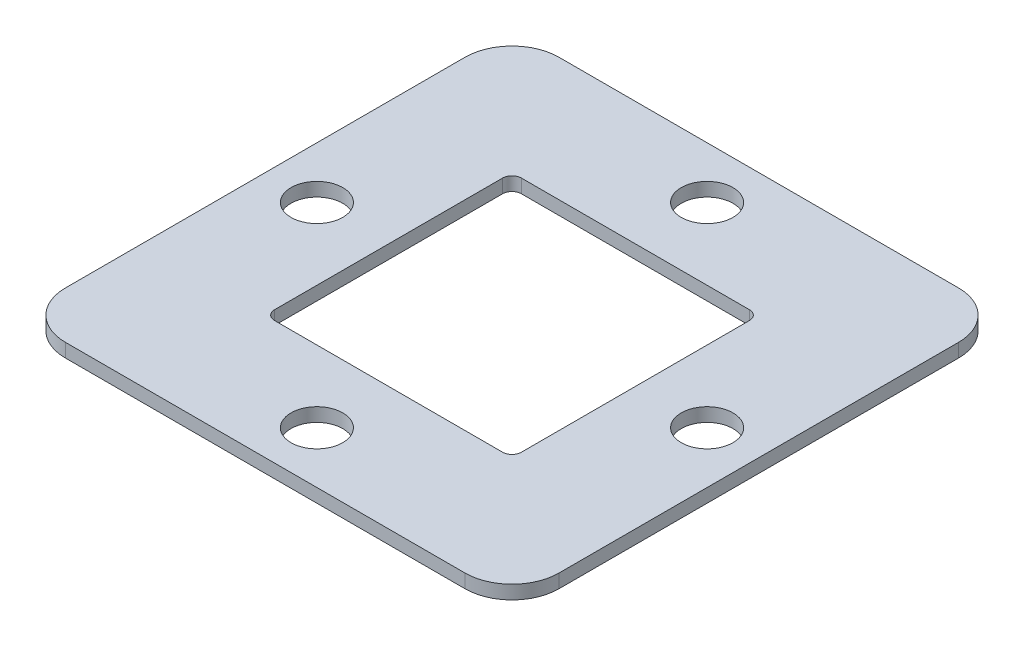
SolidWorks part; units mm, degrees
material "Custom Plastic"
ref_plane "Front Plane" through (0, 0, 0) normal (0, 0, 1) x (1, 0, 0)
ref_plane "Top Plane" through (0, 0, 0) normal (0, 1, 0) x (1, 0, 0)
ref_plane "Right Plane" through (0, 0, 0) normal (1, 0, 0) x (0, 0, -1)
sketch "Sketch1" plane through (0, 0, 0) normal (0, 1, 0) x (1, 0, 0)
  line L5 (-10.5, 10.5) -> (10.5, 10.5)
  line L6 (-10.5, 10.5) -> (-10.5, -10.5)
  line L7 (-10.5, -10.5) -> (10.5, -10.5)
  line L8 (10.5, 10.5) -> (10.5, -10.5)
  line L9 (-10.5, 10.5) -> (10.5, -10.5) construction
  line L10 (-10.5, -10.5) -> (10.5, 10.5) construction
  point P0 (0, 0)
  dimension "D1" = 21
extrude "Boss-Extrude1" add sketch "Sketch1" along normal blind 0.58
sketch "Sketch2" plane through (0, 0.58, 0) normal (0, 1, 0) x (1, 0, 0)
  line L5 (-5.25, 5.25) -> (5.25, 5.25)
  line L6 (-5.25, 5.25) -> (-5.25, -5.25)
  line L7 (-5.25, -5.25) -> (5.25, -5.25)
  line L8 (5.25, 5.25) -> (5.25, -5.25)
  line L9 (-5.25, 5.25) -> (5.25, -5.25) construction
  line L10 (-5.25, -5.25) -> (5.25, 5.25) construction
  point P0 (0, 0)
  dimension "D1" = 10.5
extrude "Cut-Extrude1" cut sketch "Sketch2" against normal through all
fillet "Fillet1" radius 2 4 edges at (-10.5, 0.29, 10.5) (-10.5, 0.29, -10.5) (10.5, 0.29, -10.5) (10.5, 0.29, 10.5)
sketch "Sketch3" plane through (0, 0.58, 0) normal (0, 1, 0) x (1, 0, 0)
  line L0 (-1000, 0) -> (49000, 0) construction
  line L1 (0, -1000) -> (0, 49000) construction
  line L2 (-1000.1511, 5.5) -> (48999.7528, 5.5) construction
  line L3 (-999.6259, -5.5) -> (49000.7521, -5.5) construction
  line L4 (-1006.7067, 2.2) -> (48970.3156, 2.2) construction
  line L5 (-995.6657, -2.2) -> (48999.0786, -2.2) construction
  line L8 (6.3218, 3.3211) -> (6.6489, 4.535)
  line L10 (5.25, 1.9) -> (5.25, 1.79)
  line L12 (7.2282, 4.3789) -> (6.9011, 3.165)
  line L43 (7.0073, 3.1364) -> (7.3345, 4.3502)
  line L45 (6.5427, 4.5636) -> (6.2155, 3.3498)
  line L48 (10.5, 6) -> (10.5, 5) construction
  line L49 (8.3, 5.91) -> (9, 6.64)
  line L137 (9, 6) -> (8.3, 5.8)
  line L138 (8.3, 5.2) -> (9, 5)
  line L140 (9, 4.36) -> (8.3, 5.09)
  line L141 (8.3, 5.8) -> (8.3, 5.2) construction
  line L224 (5.25, 2.5) -> (5.25, 1.9) construction
  line L312 (5.25, 2.61) -> (5.25, 2.5)
  line L314 (10.5, 6.64) -> (9, 6.64)
  line L315 (10.5, 6.64) -> (10.5, 6)
  line L316 (10.5, 6) -> (9, 6)
  line L319 (10.5, 5) -> (9, 5)
  line L320 (10.5, 5) -> (10.5, 4.36)
  line L321 (10.5, 4.36) -> (9, 4.36)
  line L433 (10.5, -8.5) -> (10.5, 8.5) construction
  line L434 (5.25, -5.25) -> (5.25, 5.25) construction
  line L435 (10.5, -5) -> (10.5, -4.36)
  line L436 (10.5, -5) -> (9, -5)
  line L437 (10.5, -4.36) -> (9, -4.36)
  line L438 (9, -4.36) -> (8.3, -5.09)
  line L439 (8.3, -5.2) -> (9, -5)
  line L440 (7.2282, -4.3789) -> (6.9011, -3.165)
  line L441 (7.0073, -3.1364) -> (7.3345, -4.3502)
  line L442 (5.25, -1.9) -> (5.25, -1.79)
  line L443 (5.25, -2.61) -> (5.25, -2.5)
  line L444 (6.5427, -4.5636) -> (6.2155, -3.3498)
  line L445 (6.3218, -3.3211) -> (6.6489, -4.535)
  line L446 (10.5, -6.64) -> (9, -6.64)
  line L447 (8.3, -5.91) -> (9, -6.64)
  line L448 (9, -6) -> (8.3, -5.8)
  line L449 (10.5, -6) -> (9, -6)
  line L450 (10.5, -6.64) -> (10.5, -6)
  line L451 (-5, -10.5) -> (-4.36, -10.5)
  line L452 (-5, -10.5) -> (-5, -9)
  line L453 (-4.36, -10.5) -> (-4.36, -9)
  line L454 (-4.36, -9) -> (-5.09, -8.3)
  line L455 (-5.2, -8.3) -> (-5, -9)
  line L456 (-4.3789, -7.2282) -> (-3.165, -6.9011)
  line L457 (-3.1364, -7.0073) -> (-4.3502, -7.3345)
  line L458 (-1.9, -5.25) -> (-1.79, -5.25)
  line L459 (-2.61, -5.25) -> (-2.5, -5.25)
  line L460 (-4.5636, -6.5427) -> (-3.3498, -6.2155)
  line L461 (-3.3211, -6.3218) -> (-4.535, -6.6489)
  line L462 (-6.64, -10.5) -> (-6.64, -9)
  line L463 (-5.91, -8.3) -> (-6.64, -9)
  line L464 (-6, -9) -> (-5.8, -8.3)
  line L465 (-6, -10.5) -> (-6, -9)
  line L466 (-6.64, -10.5) -> (-6, -10.5)
  line L467 (6.64, -10.5) -> (6, -10.5)
  line L468 (6.64, -10.5) -> (6.64, -9)
  line L469 (5.91, -8.3) -> (6.64, -9)
  line L470 (6, -9) -> (5.8, -8.3)
  line L471 (6, -10.5) -> (6, -9)
  line L472 (4.5636, -6.5427) -> (3.3498, -6.2155)
  line L473 (3.3211, -6.3218) -> (4.535, -6.6489)
  line L474 (2.61, -5.25) -> (2.5, -5.25)
  line L475 (1.9, -5.25) -> (1.79, -5.25)
  line L476 (4.3789, -7.2282) -> (3.165, -6.9011)
  line L477 (3.1364, -7.0073) -> (4.3502, -7.3345)
  line L478 (5.2, -8.3) -> (5, -9)
  line L479 (5, -10.5) -> (5, -9)
  line L480 (5, -10.5) -> (4.36, -10.5)
  line L481 (4.36, -10.5) -> (4.36, -9)
  line L482 (4.36, -9) -> (5.09, -8.3)
  line L483 (-10.5, 5) -> (-10.5, 4.36)
  line L484 (-10.5, 5) -> (-9, 5)
  line L485 (-10.5, 4.36) -> (-9, 4.36)
  line L486 (-9, 4.36) -> (-8.3, 5.09)
  line L487 (-8.3, 5.2) -> (-9, 5)
  line L488 (-7.2282, 4.3789) -> (-6.9011, 3.165)
  line L489 (-7.0073, 3.1364) -> (-7.3345, 4.3502)
  line L490 (-5.25, 1.9) -> (-5.25, 1.79)
  line L491 (-5.25, 2.61) -> (-5.25, 2.5)
  line L492 (-6.5427, 4.5636) -> (-6.2155, 3.3498)
  line L493 (-6.3218, 3.3211) -> (-6.6489, 4.535)
  line L494 (-10.5, 6.64) -> (-9, 6.64)
  line L495 (-8.3, 5.91) -> (-9, 6.64)
  line L496 (-9, 6) -> (-8.3, 5.8)
  line L497 (-10.5, 6) -> (-9, 6)
  line L498 (-10.5, 6.64) -> (-10.5, 6)
  line L499 (-10.5, -6.64) -> (-10.5, -6)
  line L500 (-10.5, -6.64) -> (-9, -6.64)
  line L501 (-8.3, -5.91) -> (-9, -6.64)
  line L502 (-9, -6) -> (-8.3, -5.8)
  line L503 (-10.5, -6) -> (-9, -6)
  line L504 (-6.5427, -4.5636) -> (-6.2155, -3.3498)
  line L505 (-6.3218, -3.3211) -> (-6.6489, -4.535)
  line L506 (-5.25, -2.61) -> (-5.25, -2.5)
  line L507 (-5.25, -1.9) -> (-5.25, -1.79)
  line L508 (-7.2282, -4.3789) -> (-6.9011, -3.165)
  line L509 (-7.0073, -3.1364) -> (-7.3345, -4.3502)
  line L510 (-8.3, -5.2) -> (-9, -5)
  line L511 (-10.5, -5) -> (-9, -5)
  line L512 (-10.5, -5) -> (-10.5, -4.36)
  line L513 (-10.5, -4.36) -> (-9, -4.36)
  line L514 (-9, -4.36) -> (-8.3, -5.09)
  line L515 (5, 10.5) -> (4.36, 10.5)
  line L516 (5, 10.5) -> (5, 9)
  line L517 (4.36, 10.5) -> (4.36, 9)
  line L518 (4.36, 9) -> (5.09, 8.3)
  line L519 (5.2, 8.3) -> (5, 9)
  line L520 (4.3789, 7.2282) -> (3.165, 6.9011)
  line L521 (3.1364, 7.0073) -> (4.3502, 7.3345)
  line L522 (1.9, 5.25) -> (1.79, 5.25)
  line L523 (2.61, 5.25) -> (2.5, 5.25)
  line L524 (4.5636, 6.5427) -> (3.3498, 6.2155)
  line L525 (3.3211, 6.3218) -> (4.535, 6.6489)
  line L526 (6.64, 10.5) -> (6.64, 9)
  line L527 (5.91, 8.3) -> (6.64, 9)
  line L528 (6, 9) -> (5.8, 8.3)
  line L529 (6, 10.5) -> (6, 9)
  line L530 (6.64, 10.5) -> (6, 10.5)
  line L531 (-6.64, 10.5) -> (-6, 10.5)
  line L532 (-6.64, 10.5) -> (-6.64, 9)
  line L533 (-5.91, 8.3) -> (-6.64, 9)
  line L534 (-6, 9) -> (-5.8, 8.3)
  line L535 (-6, 10.5) -> (-6, 9)
  line L536 (-4.5636, 6.5427) -> (-3.3498, 6.2155)
  line L537 (-3.3211, 6.3218) -> (-4.535, 6.6489)
  line L538 (-2.61, 5.25) -> (-2.5, 5.25)
  line L539 (-1.9, 5.25) -> (-1.79, 5.25)
  line L540 (-4.3789, 7.2282) -> (-3.165, 6.9011)
  line L541 (-3.1364, 7.0073) -> (-4.3502, 7.3345)
  line L542 (-5.2, 8.3) -> (-5, 9)
  line L543 (-5, 10.5) -> (-5, 9)
  line L544 (-5, 10.5) -> (-4.36, 10.5)
  line L545 (-4.36, 10.5) -> (-4.36, 9)
  line L546 (-4.36, 9) -> (-5.09, 8.3)
  arc A4 (8.3, 5.91) -> (6.5427, 4.5636) centre (8.3, 4.09) ccw
  arc A5 (8.3, 5.8) -> (6.6489, 4.535) centre (8.3, 4.09) ccw
  arc A6 (8.3, 5.2) -> (7.2282, 4.3789) centre (8.3, 4.09) ccw
  arc A7 (8.3, 5.09) -> (7.3345, 4.3502) centre (8.3, 4.09) ccw
  arc A36 (5.25, 1.79) -> (7.0073, 3.1364) centre (5.25, 3.61) ccw
  arc A37 (5.25, 1.9) -> (6.9011, 3.165) centre (5.25, 3.61) ccw
  arc A38 (5.25, 2.61) -> (6.2155, 3.3498) centre (5.25, 3.61) ccw
  arc A39 (5.25, 2.5) -> (6.3218, 3.3211) centre (5.25, 3.61) ccw
  arc A100 (8.3, -5.2) -> (7.2282, -4.3789) centre (8.3, -4.09) cw
  arc A101 (8.3, -5.09) -> (7.3345, -4.3502) centre (8.3, -4.09) cw
  arc A102 (5.25, -1.79) -> (7.0073, -3.1364) centre (5.25, -3.61) cw
  arc A103 (5.25, -1.9) -> (6.9011, -3.165) centre (5.25, -3.61) cw
  arc A104 (5.25, -2.61) -> (6.2155, -3.3498) centre (5.25, -3.61) cw
  arc A105 (5.25, -2.5) -> (6.3218, -3.3211) centre (5.25, -3.61) cw
  arc A106 (8.3, -5.8) -> (6.6489, -4.535) centre (8.3, -4.09) cw
  arc A107 (8.3, -5.91) -> (6.5427, -4.5636) centre (8.3, -4.09) cw
  arc A116 (-5.2, -8.3) -> (-4.3789, -7.2282) centre (-4.09, -8.3) cw
  arc A117 (-5.09, -8.3) -> (-4.3502, -7.3345) centre (-4.09, -8.3) cw
  arc A118 (-1.79, -5.25) -> (-3.1364, -7.0073) centre (-3.61, -5.25) cw
  arc A119 (-1.9, -5.25) -> (-3.165, -6.9011) centre (-3.61, -5.25) cw
  arc A120 (-2.61, -5.25) -> (-3.3498, -6.2155) centre (-3.61, -5.25) cw
  arc A121 (-2.5, -5.25) -> (-3.3211, -6.3218) centre (-3.61, -5.25) cw
  arc A122 (-5.8, -8.3) -> (-4.535, -6.6489) centre (-4.09, -8.3) cw
  arc A123 (-5.91, -8.3) -> (-4.5636, -6.5427) centre (-4.09, -8.3) cw
  arc A124 (5.91, -8.3) -> (4.5636, -6.5427) centre (4.09, -8.3) ccw
  arc A125 (5.8, -8.3) -> (4.535, -6.6489) centre (4.09, -8.3) ccw
  arc A126 (2.61, -5.25) -> (3.3498, -6.2155) centre (3.61, -5.25) ccw
  arc A127 (2.5, -5.25) -> (3.3211, -6.3218) centre (3.61, -5.25) ccw
  arc A128 (1.9, -5.25) -> (3.165, -6.9011) centre (3.61, -5.25) ccw
  arc A129 (1.79, -5.25) -> (3.1364, -7.0073) centre (3.61, -5.25) ccw
  arc A130 (5.2, -8.3) -> (4.3789, -7.2282) centre (4.09, -8.3) ccw
  arc A131 (5.09, -8.3) -> (4.3502, -7.3345) centre (4.09, -8.3) ccw
  arc A132 (-8.3, 5.2) -> (-7.2282, 4.3789) centre (-8.3, 4.09) cw
  arc A133 (-8.3, 5.09) -> (-7.3345, 4.3502) centre (-8.3, 4.09) cw
  arc A134 (-5.25, 1.79) -> (-7.0073, 3.1364) centre (-5.25, 3.61) cw
  arc A135 (-5.25, 1.9) -> (-6.9011, 3.165) centre (-5.25, 3.61) cw
  arc A136 (-5.25, 2.61) -> (-6.2155, 3.3498) centre (-5.25, 3.61) cw
  arc A137 (-5.25, 2.5) -> (-6.3218, 3.3211) centre (-5.25, 3.61) cw
  arc A138 (-8.3, 5.8) -> (-6.6489, 4.535) centre (-8.3, 4.09) cw
  arc A139 (-8.3, 5.91) -> (-6.5427, 4.5636) centre (-8.3, 4.09) cw
  arc A140 (-8.3, -5.91) -> (-6.5427, -4.5636) centre (-8.3, -4.09) ccw
  arc A141 (-8.3, -5.8) -> (-6.6489, -4.535) centre (-8.3, -4.09) ccw
  arc A142 (-5.25, -2.61) -> (-6.2155, -3.3498) centre (-5.25, -3.61) ccw
  arc A143 (-5.25, -2.5) -> (-6.3218, -3.3211) centre (-5.25, -3.61) ccw
  arc A144 (-5.25, -1.9) -> (-6.9011, -3.165) centre (-5.25, -3.61) ccw
  arc A145 (-5.25, -1.79) -> (-7.0073, -3.1364) centre (-5.25, -3.61) ccw
  arc A146 (-8.3, -5.2) -> (-7.2282, -4.3789) centre (-8.3, -4.09) ccw
  arc A147 (-8.3, -5.09) -> (-7.3345, -4.3502) centre (-8.3, -4.09) ccw
  arc A148 (5.2, 8.3) -> (4.3789, 7.2282) centre (4.09, 8.3) cw
  arc A149 (5.09, 8.3) -> (4.3502, 7.3345) centre (4.09, 8.3) cw
  arc A150 (1.79, 5.25) -> (3.1364, 7.0073) centre (3.61, 5.25) cw
  arc A151 (1.9, 5.25) -> (3.165, 6.9011) centre (3.61, 5.25) cw
  arc A152 (2.61, 5.25) -> (3.3498, 6.2155) centre (3.61, 5.25) cw
  arc A153 (2.5, 5.25) -> (3.3211, 6.3218) centre (3.61, 5.25) cw
  arc A154 (5.8, 8.3) -> (4.535, 6.6489) centre (4.09, 8.3) cw
  arc A155 (5.91, 8.3) -> (4.5636, 6.5427) centre (4.09, 8.3) cw
  arc A156 (-5.91, 8.3) -> (-4.5636, 6.5427) centre (-4.09, 8.3) ccw
  arc A157 (-5.8, 8.3) -> (-4.535, 6.6489) centre (-4.09, 8.3) ccw
  arc A158 (-2.61, 5.25) -> (-3.3498, 6.2155) centre (-3.61, 5.25) ccw
  arc A159 (-2.5, 5.25) -> (-3.3211, 6.3218) centre (-3.61, 5.25) ccw
  arc A160 (-1.9, 5.25) -> (-3.165, 6.9011) centre (-3.61, 5.25) ccw
  arc A161 (-1.79, 5.25) -> (-3.1364, 7.0073) centre (-3.61, 5.25) ccw
  arc A162 (-5.2, 8.3) -> (-4.3789, 7.2282) centre (-4.09, 8.3) ccw
  arc A163 (-5.09, 8.3) -> (-4.3502, 7.3345) centre (-4.09, 8.3) ccw
  point P19 (8.3, 5.5)
  point P20 (10.5, 5.5)
  point P24 (-3.6065, -7.7435)
  point P25 (-4.1065, -7.7435)
  point P59 (2.9086, 8.0024)
  point P62 (3.4086, 8.0024)
  point P165 (5.25, 2.2)
  point P238 (0, 0)
  dimension "D7" = 1
  dimension "D6" = 1
  dimension "D1" = 11
  dimension "D2" = 4.4
  dimension "D3" = 0.64
  dimension "D4" = 1
  dimension "D5" = 0.11
  dimension "D8" = 0.6
  dimension "D9" = 1.5
  dimension "D10" = 2.2
sketch "Sketch5" plane through (0, 0.58, 0) normal (0, 1, 0) x (1, 0, 0)
  line L1 (8.5, 10.5) -> (-8.5, 10.5) construction
  circle A0 centre (0, 8.3) radius 1.1
  circle A1 centre (0, 8.3) radius 1.85 construction
  circle A4 centre (8.3, 0) radius 1.1
  circle A6 centre (0, -8.3) radius 1.1
  circle A8 centre (-8.3, 0) radius 1.1
  point P28 (0, 0)
  dimension "D1" = 2.2
  dimension "D3" = 3.7
  dimension "D2" = 2.2
  dimension "D8" = 4
extrude "Cut-Extrude5" cut sketch "Sketch5" against normal through all
fillet "Fillet2" radius 0.4 4 edges at (-5.25, 0.29, 5.25) (5.25, 0.29, 5.25) (5.25, 0.29, -5.25) (-5.25, 0.29, -5.25)
equation "\"chip_size\"= 10mm"
equation "\"hold_edge\"= 1mm"
equation "\"cavity_size\"= \"holder_size\" - 2 * 4"
equation "\"holder_size\"= 29"
equation "\"M2P5\"= 2.5"
equation "\"height_SMA\"= 7"
equation "\"tube_SMA\"= 4mm"
equation "\"separation_SMA\"= 11"
equation "\"M2P5\"=2.5"
equation "\"via\"= 0.25"
equation "\"via_space\"= 1"
equation "\"via_gap\"= 0.5"
equation "\"D1@Sketch1\"=\"cavity_size\""
equation "\"D1@Sketch2\"=\"chip_size\"+0.5"
equation "\"w1\"= 1"
equation "\"D4@Sketch3\"=\"w1\""
equation "\"s1\"=0.64"
equation "\"D3@Sketch3\"=\"s1\""
equation "\"w2\"=0.6"
equation "\"D8@Sketch3\"=\"w2\""
equation "\"s2\"=0.11"
equation "\"D5@Sketch3\"=\"s2\""
equation "\"PCB_thickness\"= 0.51"
equation "\"PCB_Cu_thickness\"= 0.035"
equation "\"D1@Boss-Extrude1\"=\"PCB_thickness\"+2*\"PCB_Cu_thickness\""
